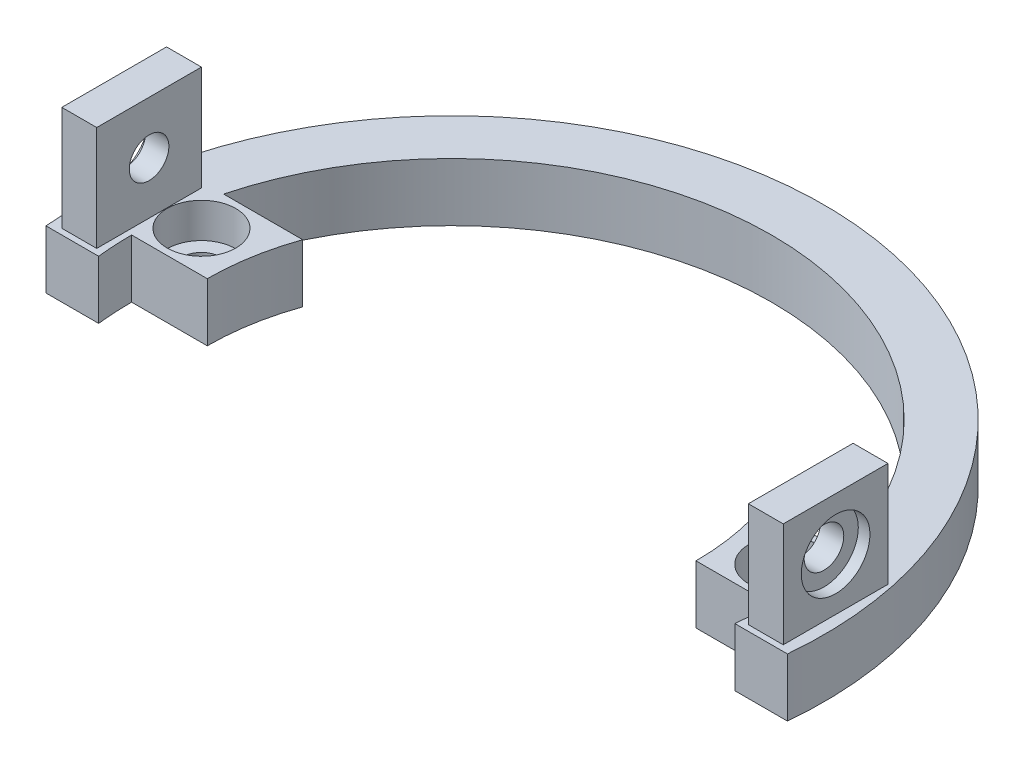
SolidWorks part; units mm, degrees
material "PLA"
ref_plane "Alzado" through (0, 0, 0) normal (0, 0, 1) x (1, 0, 0)
ref_plane "Planta" through (0, 0, 0) normal (0, 1, 0) x (1, 0, 0)
ref_plane "Vista lateral" through (0, 0, 0) normal (1, 0, 0) x (0, 0, -1)
sketch "Croquis1" plane through (0, 0, 0) normal (0, 1, 0) x (1, 0, 0)
  line L0 (-31.8591, -3) -> (-27.3359, -3)
  line L1 (27.3359, -3) -> (31.8591, -3)
  line L2 (-27.5, 0) -> (-21, 0)
  line L3 (-26.5942, 7) -> (-19.799, 7)
  line L4 (21, 0) -> (27.5, 0)
  line L5 (19.799, 7) -> (26.5942, 7)
  line L6 (0, 0) -> (-25, 3.5) construction
  line L7 (0, 0) -> (-12.5, 0) construction
  arc A0 (31.8591, -3) -> (-31.8591, -3) centre (0, 0) ccw
  arc A1 (27.3359, -3) -> (27.5, 0) centre (0, 0) ccw
  arc A2 (-19.799, 7) -> (-21, 0) centre (0, 0) ccw
  arc A3 (21, 0) -> (19.799, 7) centre (0, 0) ccw
  circle A4 centre (-25, 3.5) radius 1.7
  circle A5 centre (25, 3.5) radius 1.7
  arc A6 (-27.5, 0) -> (-27.3359, -3) centre (0, 0) ccw
  arc A7 (26.5942, 7) -> (-26.5942, 7) centre (0, 0) ccw
  dimension "D1" = 64
  dimension "D2" = 55
  dimension "D4" = 21
  dimension "D9" = 3.4
  dimension "D3" = 3
  dimension "D5" = 7
  dimension "D6" = 3.5
  dimension "D7" = 25
  dimension "D8" = 25
extrude "Saliente-Extruir1" add sketch "Croquis1" along normal blind 5
sketch "Croquis3" plane through (0, 5, 0) normal (0, 1, 0) x (1, 0, 0)
  circle A0 centre (-25, 3.5) radius 2.95
  circle A1 centre (25, 3.5) radius 2.95
  dimension "D1" = 5.9
extrude "Cortar-Extruir1" cut sketch "Croquis3" against normal blind 3
sketch "Sketch1" plane through (0, 5, 0) normal (0, 1, 0) x (1, 0, 0)
  line L0 (-31, 6.5) -> (-28, 6.5)
  line L1 (-31, 6.5) -> (-31, -2.5)
  line L2 (-28, 6.5) -> (-28, -2.5)
  line L3 (-31, -2.5) -> (-28, -2.5)
  line L4 (0, 0) -> (0, 23.167) construction
  line L5 (28, 6.5) -> (28, -2.5)
  line L6 (31, -2.5) -> (28, -2.5)
  line L7 (31, 6.5) -> (31, -2.5)
  line L8 (31, 6.5) -> (28, 6.5)
  line L9 (0, 0) -> (-28, 6.5) construction
  line L10 (0, 0) -> (-21, 0) construction
  line L11 (-28, -2.5) -> (0, 0)
  circle A0 centre (-25, 3.5) radius 1.7 construction
  dimension "D5" = 13.069
  dimension "D1" = 28
  dimension "D2" = 31
  dimension "D3" = 9
  dimension "D4" = 3
  dimension "D6" = 18.171
extrude "Boss-Extrude1" add sketch "Sketch1" along normal blind 9 contours L1 L3 L2 L0 | L7 L8 L5 L6
sketch "Sketch2" plane through (-31, 0, 0) normal (-1, 0, 0) x (0, 0, 1)
  line L0 (2.5, 5) -> (-6.5, 5)
  line L1 (2.5, 14) -> (2.5, 5) construction
  circle A0 centre (-2, 9.5) radius 1.7
  circle A1 centre (-2, 9.5) radius 3.35 construction
  dimension "D2" = 3.4
  dimension "D3" = 6.7
  dimension "D1" = 4.5
  dimension "D4" = 4.5
extrude "Cut-Extrude3" cut sketch "Sketch2" against normal blind 73 and the other way blind 10 contours A0
sketch "Sketch4" plane through (-31, 0, 0) normal (-1, 0, 0) x (0, 0, 1)
  circle A0 centre (-2, 9.5) radius 2.95
  dimension "D1" = 5.9
extrude "Cut-Extrude4" cut sketch "Sketch4" against normal blind 1
sketch "Sketch5" plane through (31, 0, 0) normal (1, 0, 0) x (0, 0, -1)
  circle A0 centre (2, 9.5) radius 2.95
  dimension "D1" = 5.9
extrude "Cut-Extrude5" cut sketch "Sketch5" against normal blind 1
